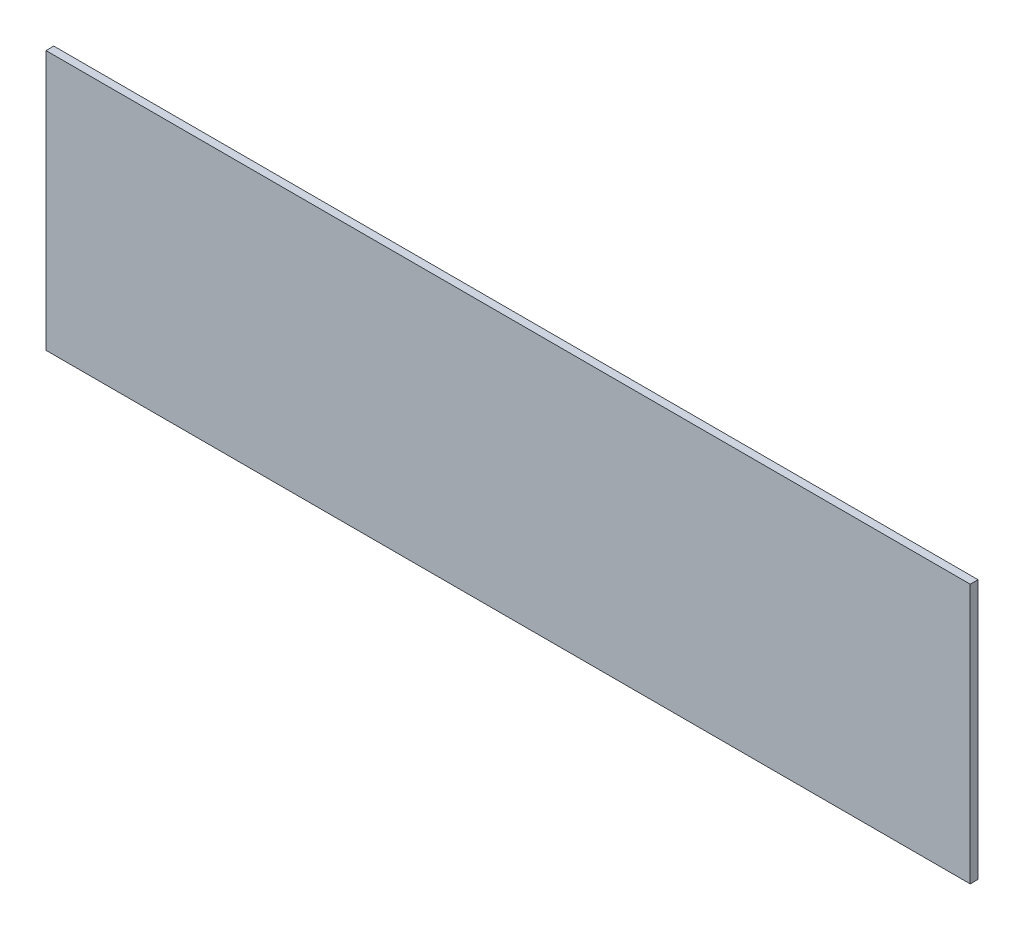
SolidWorks part; units mm, degrees
ref_plane "Plan de face" through (0, 0, 0) normal (0, 0, 1) x (1, 0, 0)
ref_plane "Plan de dessus" through (0, 0, 0) normal (0, 1, 0) x (1, 0, 0)
ref_plane "Plan de droite" through (0, 0, 0) normal (1, 0, 0) x (0, 0, -1)
sketch "Esquisse1" plane through (0, 0, 0) normal (0, 0, 1) x (1, 0, 0)
  line L1 (-187.8029, 83.0667) -> (168.1971, 83.0667)
  line L2 (-187.8029, 83.0667) -> (-187.8029, -16.9333)
  line L3 (-187.8029, -16.9333) -> (168.1971, -16.9333)
  line L4 (168.1971, 83.0667) -> (168.1971, -16.9333)
  dimension "D1" = 356
  dimension "D2" = 100
extrude "Boss.-Extru.1" add sketch "Esquisse1" along normal blind 3
